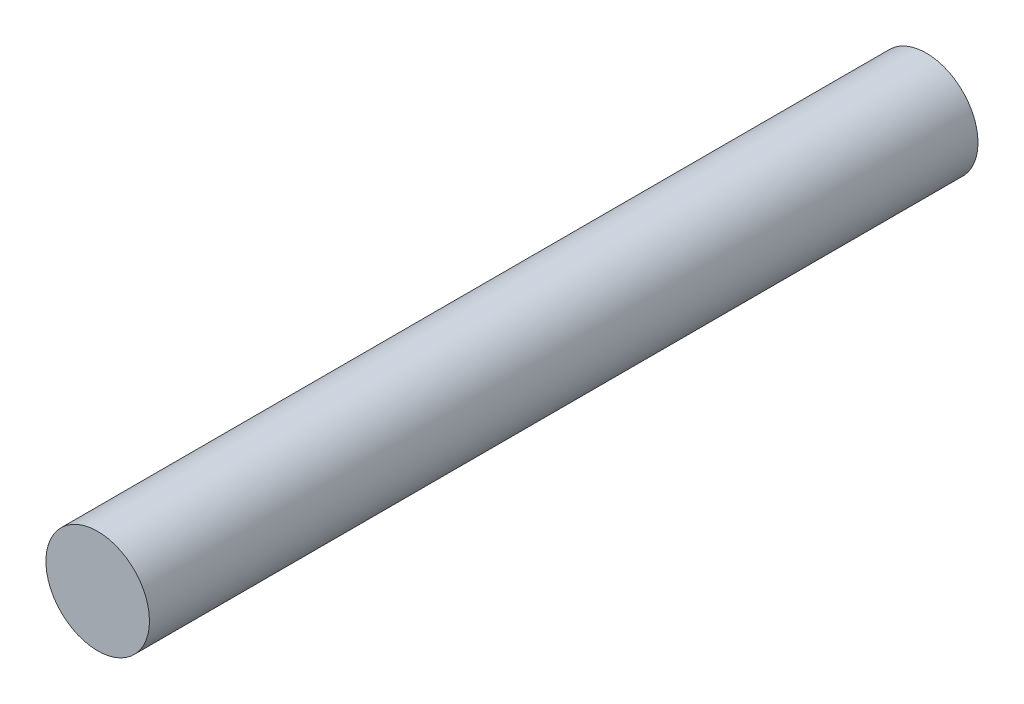
SolidWorks part; units mm, degrees
ref_plane "Front Plane" through (0, 0, 0) normal (0, 0, 1) x (1, 0, 0)
ref_plane "Top Plane" through (0, 0, 0) normal (0, 1, 0) x (1, 0, 0)
ref_plane "Right Plane" through (0, 0, 0) normal (1, 0, 0) x (0, 0, -1)
sketch "Sketch1" plane through (0, 0, 0) normal (0, 0, 1) x (1, 0, 0)
  circle A0 centre (-5.1467, 5.6335) radius 3.175
  dimension "D1" = 6.35
extrude "Boss-Extrude1" add sketch "Sketch1" along normal blind 50.8
